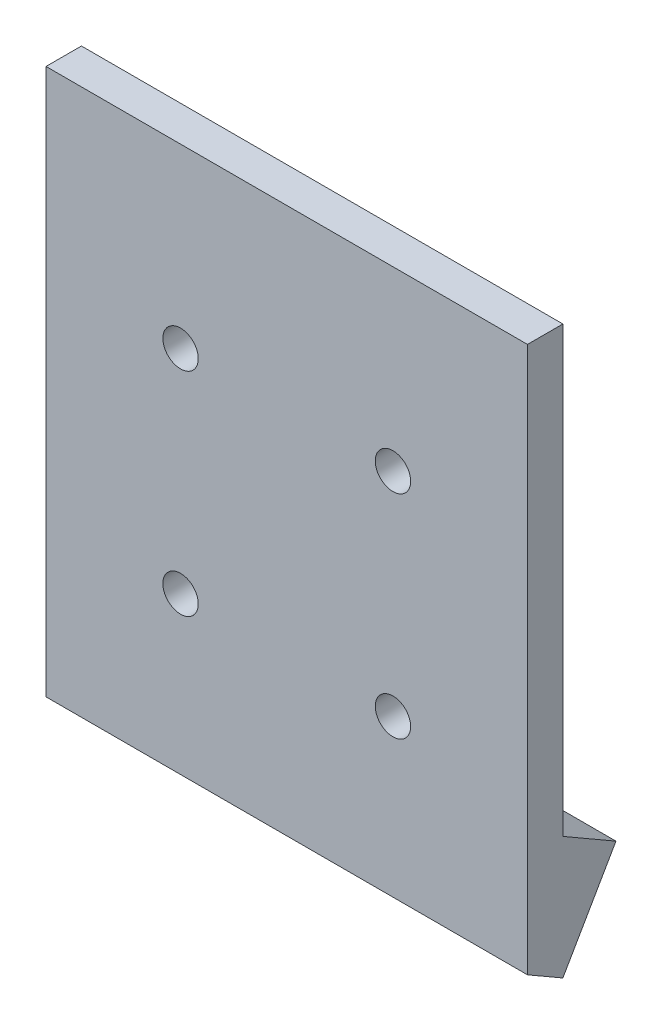
SolidWorks part; units mm, degrees
ref_plane "Front Plane" through (0, 0, 0) normal (0, 0, 1) x (1, 0, 0)
ref_plane "Top Plane" through (0, 0, 0) normal (0, 1, 0) x (1, 0, 0)
ref_plane "Right Plane" through (0, 0, 0) normal (1, 0, 0) x (0, 0, -1)
sketch "Sketch1" plane through (0, 0, 0) normal (0, 0, 1) x (1, 0, 0)
  line L0 (-19.05, 19.05) -> (19.05, 19.05) construction
  line L1 (-43.18, -50.8) -> (43.18, -50.8)
  line L2 (-43.18, -50.8) -> (-43.18, 50.8)
  line L3 (-43.18, 50.8) -> (43.18, 50.8)
  line L4 (43.18, -50.8) -> (43.18, 50.8)
  line L5 (-43.18, -50.8) -> (43.18, 50.8) construction
  line L6 (-43.18, 50.8) -> (43.18, -50.8) construction
  line L7 (19.05, 19.05) -> (19.05, -19.05) construction
  line L8 (19.05, -19.05) -> (-19.05, -19.05) construction
  line L9 (-19.05, -19.05) -> (-19.05, 19.05) construction
  line L10 (-19.05, 19.05) -> (19.05, -19.05) construction
  line L11 (19.05, 19.05) -> (-19.05, -19.05) construction
  circle A0 centre (-19.05, 19.05) radius 3.175
  circle A1 centre (19.05, 19.05) radius 3.175
  circle A2 centre (-19.05, -19.05) radius 3.175
  circle A3 centre (19.05, -19.05) radius 3.175
  point P0 (0, 0)
  point P14 (0, 0)
  dimension "D1" = 6.35
  dimension "D2" = 38.1
  dimension "D3" = 38.1
  dimension "D4" = 86.36
  dimension "D5" = 101.6
extrude "Boss-Extrude1" add sketch "Sketch1" along normal blind 6.35
sketch "Sketch2" plane through (43.18, 0, 0) normal (1, 0, 0) x (0, 0, -1)
  line L0 (0, -50.8) -> (-6.35, -47.1338)
  line L1 (-6.35, -50.8) -> (-6.35, 50.8) construction
  line L2 (-6.35, -47.1338) -> (-6.35, -50.8)
  line L3 (-6.35, -50.8) -> (0, -50.8)
  dimension "D1" = 30
extrude "Cut-Extrude1" cut sketch "Sketch2" against normal through all
sketch "Sketch3" plane through (43.18, 0, 0) normal (1, 0, 0) x (0, 0, -1)
  line L0 (0, -50.8) -> (9.525, -34.3022)
  line L1 (9.525, -34.3022) -> (0, -28.803)
  line L2 (0, -50.8) -> (0, 50.8) construction
  line L3 (0, -28.803) -> (0, -50.8)
  line L4 (0, -50.8) -> (-6.35, -47.1338) construction
  dimension "D1" = 30
  dimension "D2" = 19.05
extrude "Boss-Extrude2" add sketch "Sketch3" against normal through all
sketch "Sketch4" plane through (0, -38.1, 21.997) normal (0, -0.866, 0.5) x (-1, 0, 0)
  line L0 (-43.18, 21.7338) -> (43.18, 21.7338) construction
  line L1 (-43.18, 25.4) -> (-43.18, 18.0677) construction
  line L2 (43.18, 25.4) -> (43.18, 18.0677) construction
  circle A0 centre (31.75, 21.7338) radius 2.1828
  circle A1 centre (-31.75, 21.7338) radius 2.1828
  point P10 (0, 0)
  dimension "D1" = 63.5
  dimension "D3" = 4.3656
  dimension "D2" = 11.43
extrude "Cut-Extrude2" cut sketch "Sketch4" against normal through all
